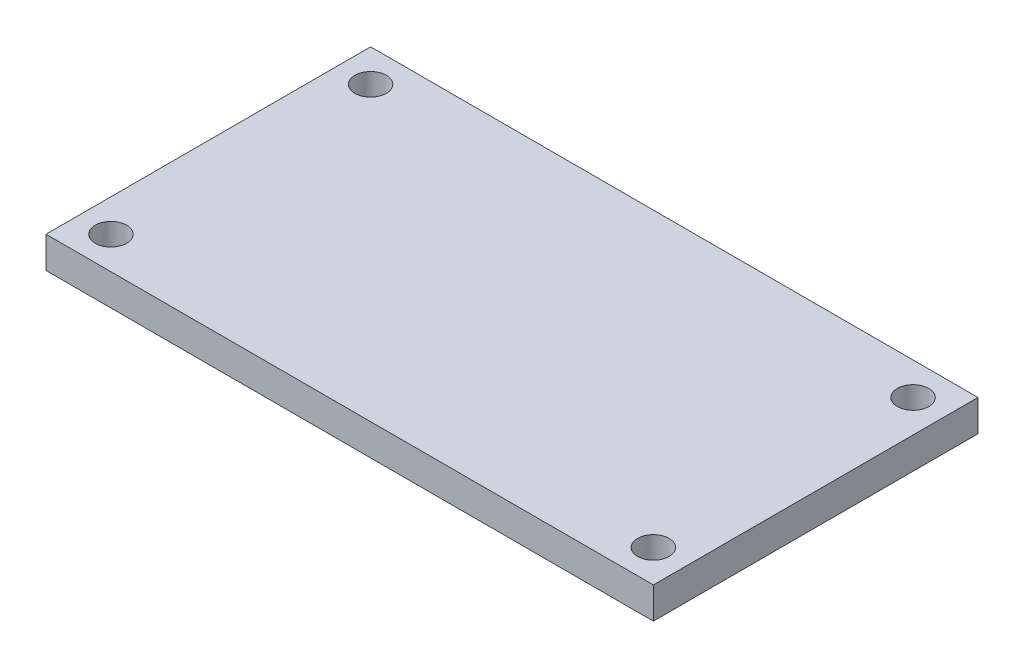
SolidWorks part; units mm, degrees
ref_plane "Front Plane" through (0, 0, 0) normal (0, 0, 1) x (1, 0, 0)
ref_plane "Top Plane" through (0, 0, 0) normal (0, 1, 0) x (1, 0, 0)
ref_plane "Right Plane" through (0, 0, 0) normal (1, 0, 0) x (0, 0, -1)
sketch "Sketch1" plane through (0, 0, 0) normal (0, 1, 0) x (1, 0, 0)
  line L1 (-29, 15.5) -> (29, 15.5)
  line L2 (-29, 15.5) -> (-29, -15.5)
  line L3 (-29, -15.5) -> (29, -15.5)
  line L4 (29, 15.5) -> (29, -15.5)
  line L5 (-29, 15.5) -> (29, -15.5) construction
  line L6 (-29, -15.5) -> (29, 15.5) construction
  point P0 (0, 0)
  dimension "D1" = 58
  dimension "D2" = 31
extrude "Boss-Extrude1" add sketch "Sketch1" along normal blind 3
sketch "Sketch2" plane through (0, 3, 0) normal (0, 1, 0) x (1, 0, 0)
  line L0 (-29, 15.5) -> (-29, -15.5) construction
  line L1 (29, 15.5) -> (-29, 15.5) construction
  circle A0 centre (-25.9, 12.4) radius 1.5
  dimension "D1" = 3
  dimension "D2" = 3.1
  dimension "D3" = 3.1
extrude "Cut-Extrude1" cut sketch "Sketch2" against normal through all
mirror "Mirror1" about plane through (0, 0, 0) normal (0, 0, 1) of "Cut-Extrude1"
mirror "Mirror2" about plane through (0, 0, 0) normal (1, 0, 0) of "Mirror1", "Cut-Extrude1"
